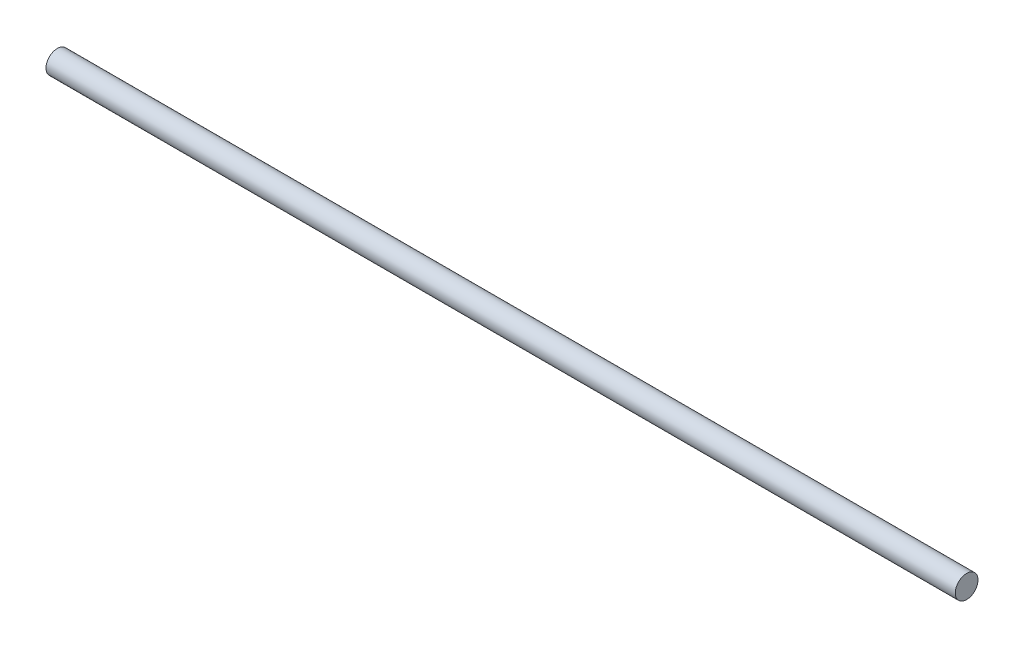
SolidWorks part; units mm, degrees
material "Hexcel AS4C (3000 丝)"
ref_plane "前视基准面" through (0, 0, 0) normal (0, 0, 1) x (1, 0, 0)
ref_plane "上视基准面" through (0, 0, 0) normal (0, 1, 0) x (1, 0, 0)
ref_plane "右视基准面" through (0, 0, 0) normal (1, 0, 0) x (0, 0, -1)
sketch "草图1" plane through (0, 0, 0) normal (1, 0, 0) x (0, 0, -1)
  circle A0 centre (0, 0) radius 0.5
  dimension "D1" = 1
extrude "凸台-拉伸1" add sketch "草图1" along normal blind 40
